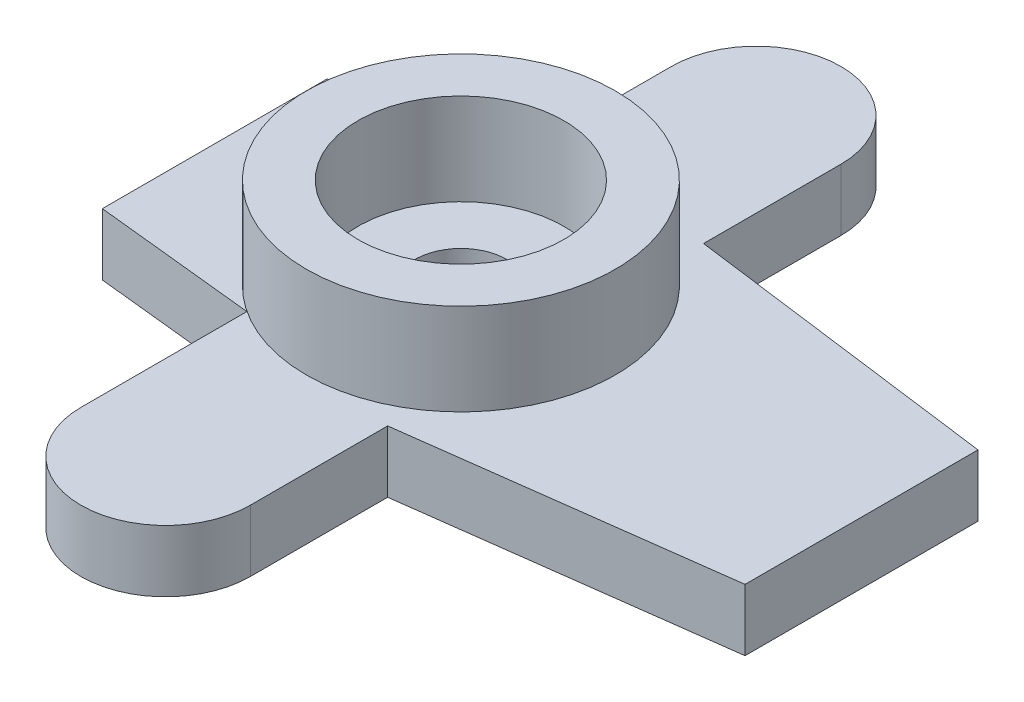
SolidWorks part; units mm, degrees
ref_plane "Piano frontale" through (0, 0, 0) normal (0, 0, 1) x (1, 0, 0)
ref_plane "Piano superiore" through (0, 0, 0) normal (0, 1, 0) x (1, 0, 0)
ref_plane "Piano destro" through (0, 0, 0) normal (1, 0, 0) x (0, 0, -1)
sketch "Schizzo1" plane through (0, 0, 0) normal (0, 1, 0) x (1, 0, 0)
  line L0 (-1.8466, 2.825) -> (-14.5, 1.5)
  line L1 (-1.8466, -2.825) -> (-14.5, -1.5)
  line L2 (-1.8466, 2.825) -> (-1.8466, -2.825)
  line L3 (0, -6.45) -> (0, 6.45) construction
  line L5 (1.85, -3.45) -> (16.7, -1.5)
  line L6 (1.85, 3.45) -> (16.7, 1.5)
  line L7 (-1.85, -6.45) -> (-1.85, 6.45)
  line L8 (1.85, -6.45) -> (1.85, 6.45)
  line L9 (8.75, -2.5439) -> (8.75, 2.5439)
  line L10 (-5.375, -2.4555) -> (-5.375, 2.4555)
  circle A0 centre (0, 0) radius 3.375
  arc A1 (-14.5, 1.5) -> (-14.5, -1.5) centre (-14.5, 0) ccw
  arc A2 (16.7, 1.5) -> (16.7, -1.5) centre (16.7, 0) cw
  arc A3 (-1.85, -6.45) -> (1.85, -6.45) centre (0, -6.45) ccw
  arc A4 (1.85, 6.45) -> (-1.85, 6.45) centre (0, 6.45) ccw
  point P8 (-1.8466, 0)
  point P14 (18.2, 0)
  point P19 (0, 0)
  point P25 (-16, 0)
  point P31 (0, 8.3)
  point P32 (0, -8.3)
  dimension "D1" = 6.75
  dimension "D3" = 1.5
  dimension "D7" = 1.5
  dimension "D2" = 5.65
  dimension "D4" = 3
  dimension "D5" = 16
  dimension "D6" = 6.9
  dimension "D8" = 3
  dimension "D9" = 34.2
  dimension "D10" = 3.7
  dimension "D11" = 16.6
  dimension "D12" = 8.75
  dimension "D13" = 5.375
extrude "Estrusione-Estrusione1" add sketch "Schizzo1" along normal blind 1.35
sketch "Schizzo2" plane through (0, 1.35, 0) normal (0, 1, 0) x (1, 0, 0)
  circle A2 centre (0, 0) radius 3.375
  dimension "D1" = 6.75
extrude "Estrusione-Estrusione2" add sketch "Schizzo2" along normal blind 2 contours A2
sketch "Schizzo3" plane through (0, 3.35, 0) normal (0, 1, 0) x (1, 0, 0)
  circle A0 centre (0, 0) radius 2.25
  dimension "D1" = 4.5
extrude "Taglio-Estrusione1" cut sketch "Schizzo3" against normal blind 2
sketch "Schizzo4" plane through (0, 1.35, 0) normal (0, 1, 0) x (1, 0, 0)
  circle A0 centre (0, 0) radius 1
  dimension "D1" = 2
extrude "Taglio-Estrusione2" cut sketch "Schizzo4" against normal through all
